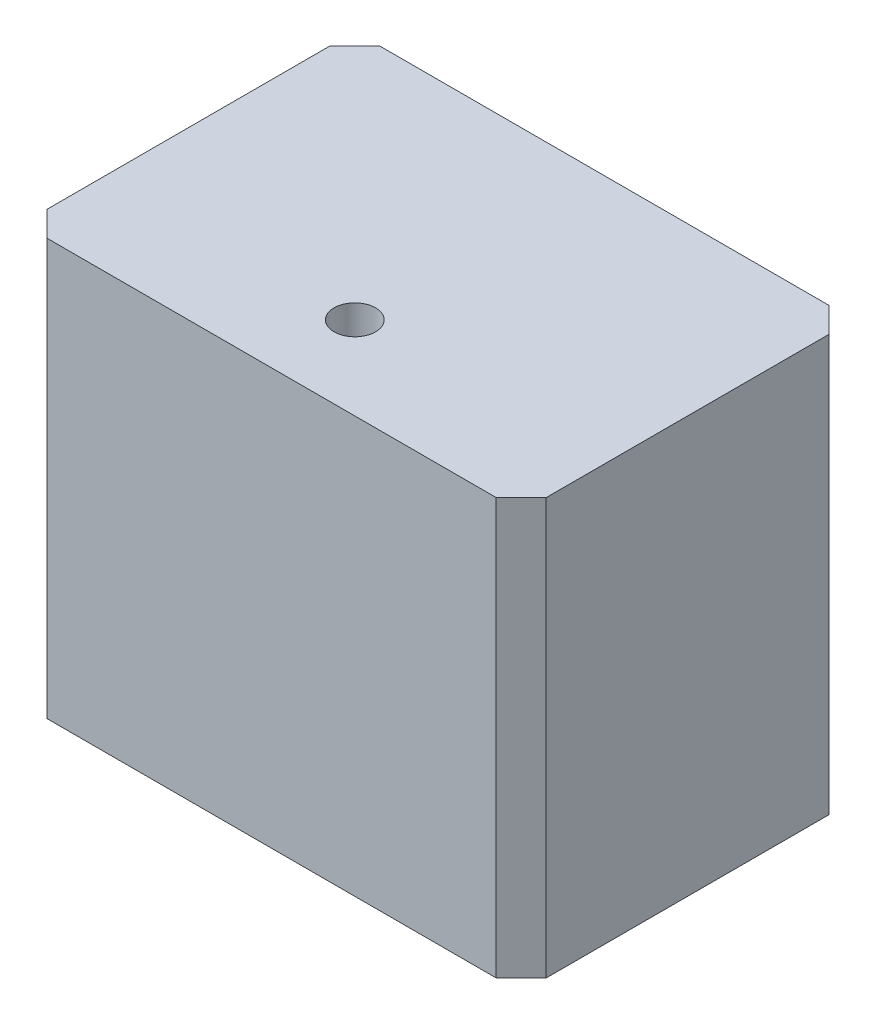
SolidWorks part; units mm, degrees
ref_plane "Front" through (0, 0, 0) normal (0, 0, 1) x (1, 0, 0)
ref_plane "Top" through (0, 0, 0) normal (0, 1, 0) x (1, 0, 0)
ref_plane "Right" through (0, 0, 0) normal (1, 0, 0) x (0, 0, -1)
sketch "草图1" plane through (0, 0, 0) normal (0, 1, 0) x (1, 0, 0)
  line L1 (15, -10) -> (-15, -10)
  line L2 (15, -10) -> (15, 10)
  line L3 (15, 10) -> (-15, 10)
  line L4 (-15, -10) -> (-15, 10)
  line L5 (15, -10) -> (-15, 10) construction
  line L6 (15, 10) -> (-15, -10) construction
  point P0 (0, 0)
  dimension "D1" = 30
  dimension "D2" = 20
extrude "凸台-拉伸1" add sketch "草图1" along normal blind 25
sketch "草图2" plane through (0, 25, 0) normal (0, 1, 0) x (1, 0, 0)
  line L0 (0, 10) -> (0, -10) construction
  line L1 (15, 10) -> (-15, 10) construction
  line L2 (-15, -10) -> (15, -10) construction
  circle A0 centre (0, -5) radius 1.25
  dimension "D1" = 2.5
  dimension "D2" = 5
extrude "切除-拉伸1" cut sketch "草图2" against normal through all
chamfer "倒角1" distance 1.5 angle 45 4 edges at (-15, 12.5, -10) (15, 12.5, -10) (-15, 12.5, 10) (15, 12.5, 10)
